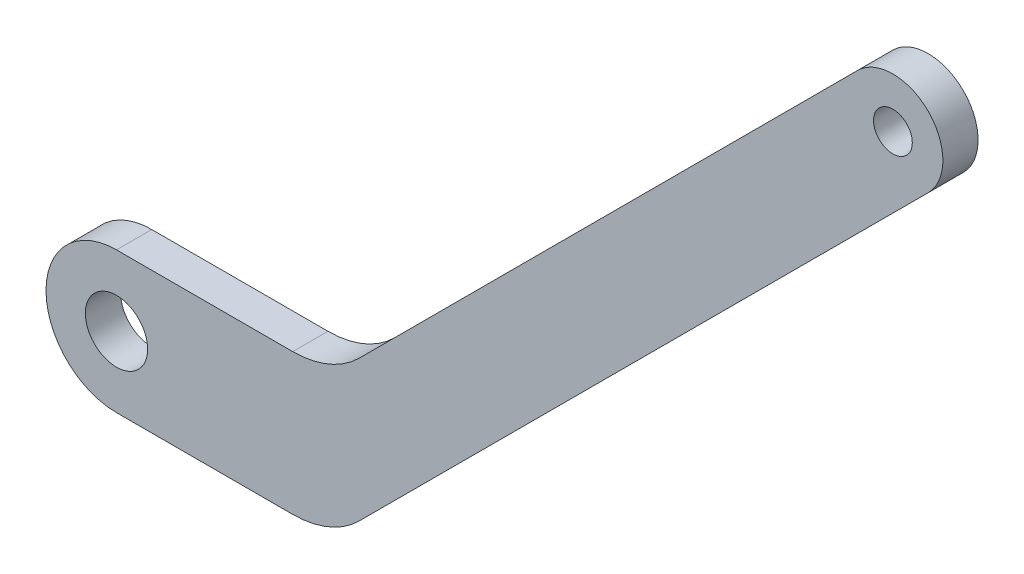
SolidWorks part; units mm, degrees
ref_plane "前视基准面" through (0, 0, 0) normal (0, 0, 1) x (1, 0, 0)
ref_plane "上视基准面" through (0, 0, 0) normal (0, 1, 0) x (1, 0, 0)
ref_plane "右视基准面" through (0, 0, 0) normal (1, 0, 0) x (0, 0, -1)
sketch "草图1" plane through (0, 0, 0) normal (0, 0, 1) x (1, 0, 0)
  line L2 (0.0002, 5.9998) -> (14.9998, 5.9998)
  line L3 (0.0002, -6.0002) -> (15.0002, -6.0002)
  line L6 (20.6559, -3.6583) -> (69.0937, 44.7591)
  line L12 (63.0833, 50.7696) -> (20.6569, 8.3431)
  arc A1 (0.0002, 5.9998) -> (0.0002, -6.0002) centre (0.0002, -0.0002) ccw
  arc A2 (14.9998, 5.9998) -> (20.6569, 8.3431) centre (14.9998, 13.9998) ccw
  arc A3 (15.0002, -6.0002) -> (20.6559, -3.6583) centre (15.0002, 1.9998) ccw
  arc A8 (63.0833, 50.7696) -> (69.0937, 44.7591) centre (66.0885, 47.7643) cw
extrude "凸台-拉伸1" add sketch "草图1" along normal blind 3
sketch "草图9" plane through (0, 0, 3) normal (0, 0, 1) x (1, 0, 0)
  circle A0 centre (0, 0) radius 2.65
  circle A1 centre (66.0885, 47.7643) radius 1.65
  point P3 (66.0885, 47.7643)
  dimension "D1" = 5.3
  dimension "D2" = 3.3
extrude "切除-拉伸5" cut sketch "草图9" against normal blind 6
